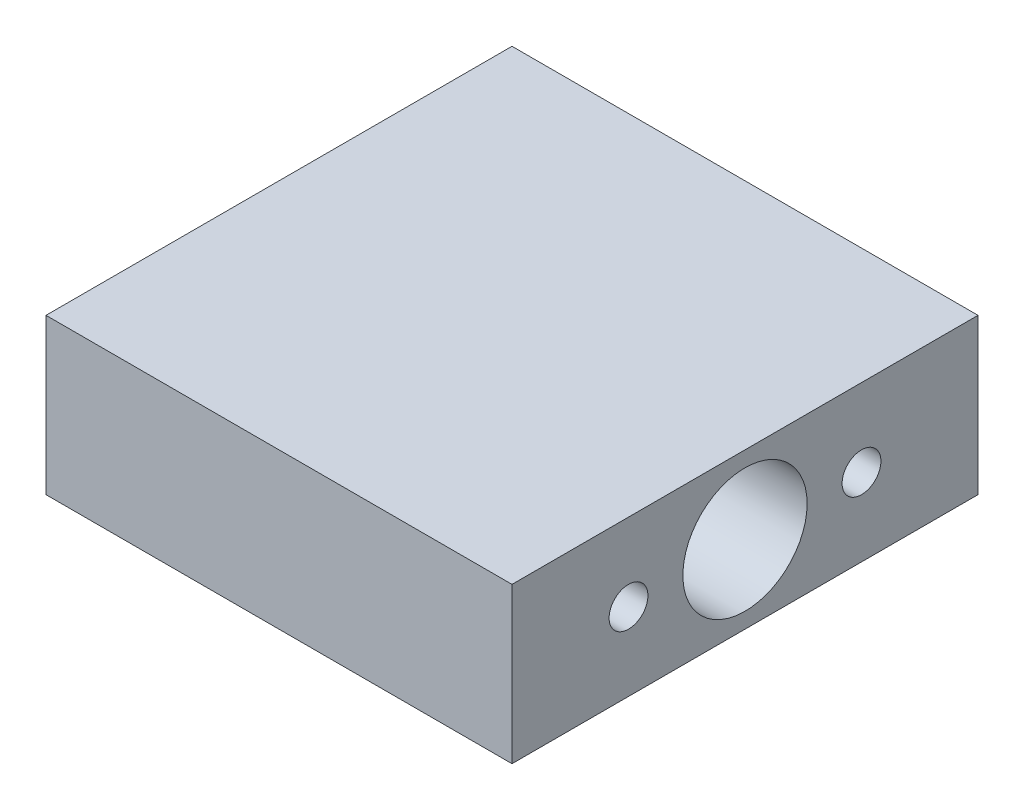
SolidWorks part; units mm, degrees
ref_plane "Front Plane" through (0, 0, 0) normal (0, 0, 1) x (1, 0, 0)
ref_plane "Top Plane" through (0, 0, 0) normal (0, 1, 0) x (1, 0, 0)
ref_plane "Right Plane" through (0, 0, 0) normal (1, 0, 0) x (0, 0, -1)
sketch "Sketch1" plane through (0, 0, 0) normal (1, 0, 0) x (0, 0, -1)
  line L1 (0, 0) -> (38.1, 0)
  line L2 (0, 0) -> (0, 12.7)
  line L3 (0, 12.7) -> (38.1, 12.7)
  line L4 (38.1, 0) -> (38.1, 12.7)
  dimension "D1" = 12.7
  dimension "D2" = 38.1
extrude "Boss-Extrude1" add sketch "Sketch1" along normal blind 38.1
sketch "Sketch2" plane through (38.1, 0, 0) normal (1, 0, 0) x (0, 0, -1)
  line L0 (0, 6.35) -> (42.0917, 6.35) construction
  line L1 (0, 12.7) -> (0, 0) construction
  line L2 (19.05, 0) -> (19.05, 14.356) construction
  line L3 (0, 0) -> (38.1, 0) construction
  circle A0 centre (19.05, 6.35) radius 5.08
  circle A1 centre (9.525, 6.35) radius 1.5875
  circle A2 centre (28.575, 6.35) radius 1.5875
  point P8 (19.05, 6.35)
  dimension "D1" = 19.05
extrude "Cut-Extrude1" cut sketch "Sketch2" against normal through all
